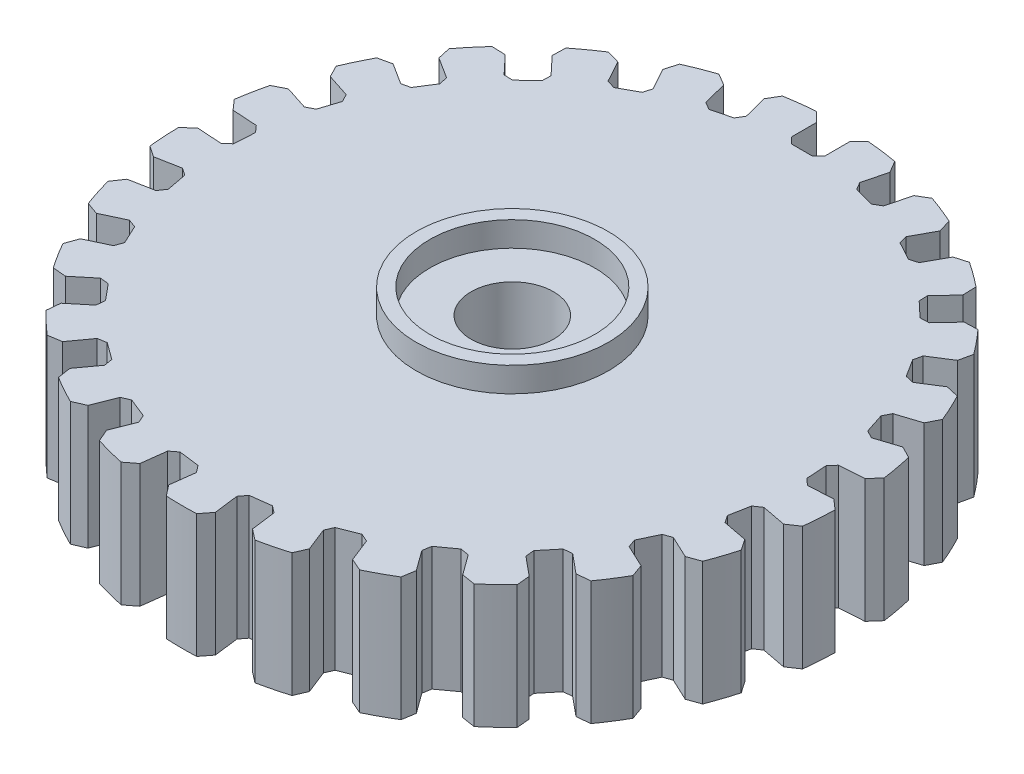
SolidWorks part; units mm, degrees
ref_plane "Alzado" through (0, 0, 0) normal (0, 0, 1) x (1, 0, 0)
ref_plane "Planta" through (0, 0, 0) normal (0, 1, 0) x (1, 0, 0)
ref_plane "Vista lateral" through (0, 0, 0) normal (1, 0, 0) x (0, 0, -1)
sketch "Croquis4" plane through (0, 0, 0) normal (0, 1, 0) x (1, 0, 0)
  circle A0 centre (0, 0) radius 40
extrude "Saliente-Extruir2" add sketch "Croquis4" along normal blind 15
sketch "Croquis5" plane through (0, 0, 0) normal (0, 1, 0) x (1, 0, 0)
  line L0 (0, 40) -> (0, 34.9487)
  line L1 (0, 34.9487) -> (0, 0)
  line L2 (0, 34.9487) -> (1.4491, 34.9487)
  line L3 (1.4491, 34.9487) -> (2.2029, 35.7025)
  line L4 (2.2029, 35.7025) -> (2.2029, 38.715)
  line L5 (2.2029, 38.715) -> (3.3475, 39.8597)
  line L6 (0, 34.9487) -> (-1.0731, 34.9487)
  line L7 (-1.0731, 34.9487) -> (-1.827, 35.7025)
  line L8 (-1.827, 35.7025) -> (-1.827, 38.715)
  line L9 (-1.827, 38.715) -> (-2.9993, 39.8874)
  line L10 (-2.9993, 39.8874) -> (0, 40.8256)
  line L11 (0, 40.8256) -> (3.3475, 39.8597)
  circle A0 centre (0, 0) radius 40 construction
extrude "Cortar-Extruir1" cut sketch "Croquis5" along normal blind 22 contours L2 L3 L4 L5 L11 L10 L9 L8 L7 L6
pattern_circular "MatrizC1" count 25 over 360 about axis through (0, 0, 0) along (0, 1, 0) of "Cortar-Extruir1"
sketch "Croquis7" plane through (0, 0, 0) normal (0, 1, 0) x (1, 0, 0)
  circle A0 centre (0, 0) radius 11.6524
  circle A1 centre (0, 0) radius 10
extrude "Saliente-Extruir4" add sketch "Croquis7" along normal blind 18 and the other way blind 3
sketch "Croquis10" plane through (0, 0, 0) normal (0, 1, 0) x (1, 0, 0)
  circle A0 centre (0, 0) radius 5
extrude "Cortar-Extruir2" cut sketch "Croquis10" along normal blind 28 and the other way blind 32
